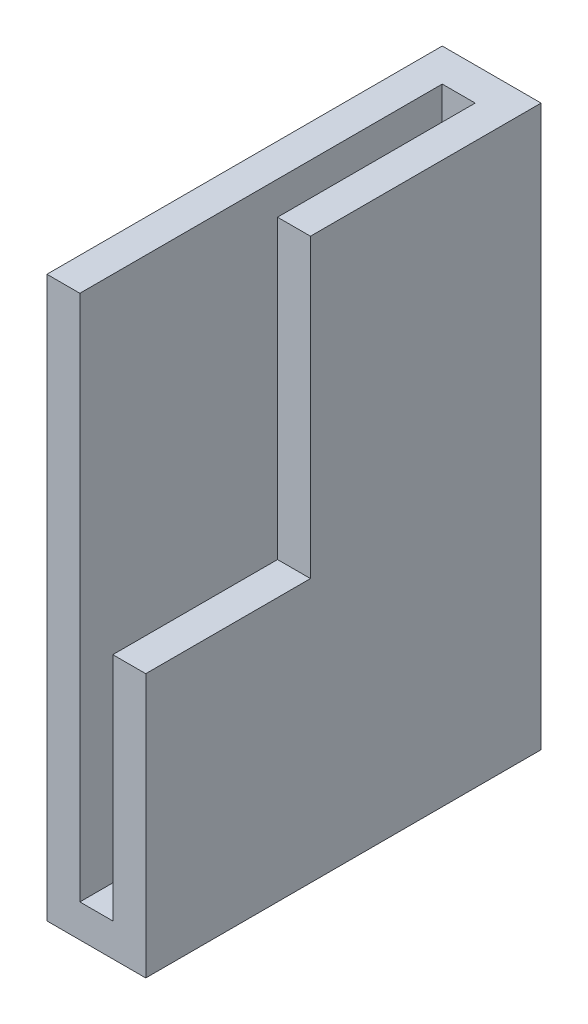
SolidWorks part; units mm, degrees
ref_plane "Front Plane" through (0, 0, 0) normal (0, 0, 1) x (1, 0, 0)
ref_plane "Top Plane" through (0, 0, 0) normal (0, 1, 0) x (1, 0, 0)
ref_plane "Right Plane" through (0, 0, 0) normal (1, 0, 0) x (0, 0, -1)
sketch "Sketch1" plane through (0, 0, 0) normal (1, 0, 0) x (0, 0, -1)
  line L1 (0, 0) -> (12, 0)
  line L2 (0, 0) -> (0, -17)
  line L3 (0, -17) -> (12, -17)
  line L4 (12, 0) -> (12, -17)
  dimension "D1" = 12
  dimension "D2" = 17
extrude "Boss-Extrude1" add sketch "Sketch1" along normal blind 3
sketch "Sketch3" plane through (0, 0, 0) normal (0, 1, 0) x (1, 0, 0)
  line L0 (3, 0) -> (0, 0) construction
  line L1 (1, 0) -> (2, 0)
  line L2 (1, 0) -> (1, 11)
  line L3 (1, 11) -> (2, 11)
  line L4 (2, 0) -> (2, 11)
  line L5 (0, 12) -> (0, 0) construction
  line L6 (3, 12) -> (0, 12) construction
  line L7 (3, 12) -> (3, 0) construction
  dimension "D1" = 1
  dimension "D2" = 1
  dimension "D3" = 1
extrude "Cut-Extrude1" cut sketch "Sketch3" against normal blind 16
sketch "Sketch2" plane through (3, 0, 0) normal (1, 0, 0) x (0, 0, -1)
  line L1 (0, 0) -> (5, 0)
  line L2 (0, 0) -> (0, -9)
  line L3 (0, -9) -> (5, -9)
  line L4 (5, 0) -> (5, -9)
  dimension "D1" = 5
  dimension "D2" = 9
extrude "Cut-Extrude2" cut sketch "Sketch2" against normal up to next
equation "\"housingWidth\"= \"PCBWidth\" + \"wallThickness\""
equation "\"D1@Sketch1\"=\"housingWidth\""
equation "\"housingHeight\" = \"PCBHeight\" + \"wallThickness\""
equation "\"D2@Sketch1\"=\"housingHeight\""
equation "\"housingDepth\"= \"PCBThickness\" + \"wallThickness\" * 2"
equation "\"D1@Boss-Extrude1\"=\"housingDepth\""
equation "\"wallThickness\"= 1"
equation "\"D1@Sketch3\"=\"wallThickness\""
equation "\"D2@Sketch3\"=\"wallThickness\""
equation "\"D3@Sketch3\"=\"wallThickness\""
equation "\"D1@Cut-Extrude1\"=\"housingHeight\"-\"wallThickness\""
equation "\"PCBWidth\"= 11"
equation "\"PCBHeight\"= 16"
equation "\"PCBThickness\"= 1mm"
